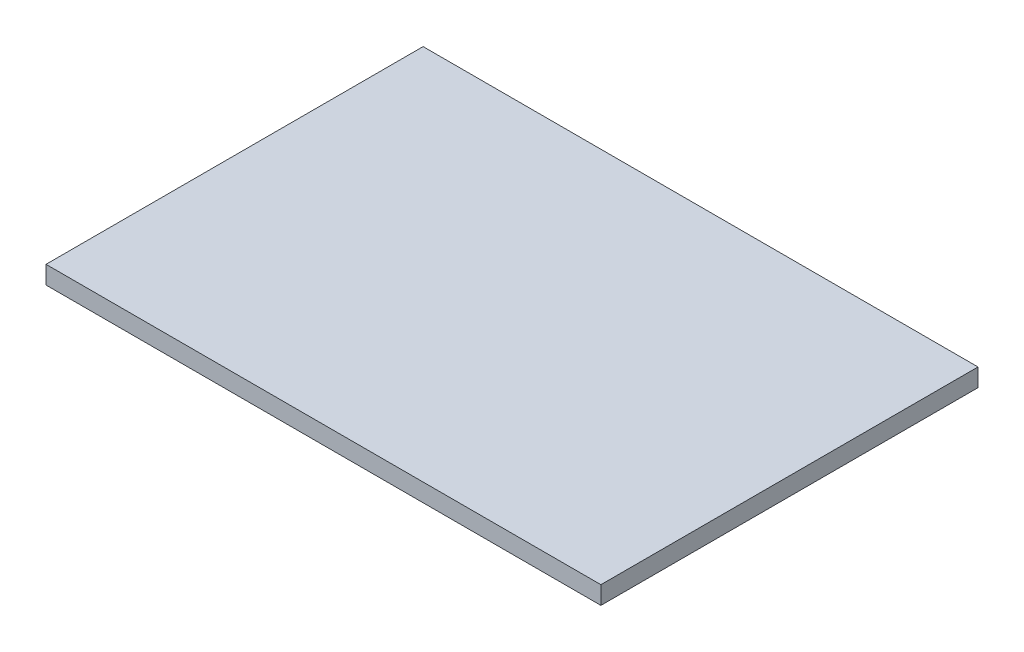
SolidWorks part; units mm, degrees
ref_plane "Front Plane" through (0, 0, 0) normal (0, 0, 1) x (1, 0, 0)
ref_plane "Top Plane" through (0, 0, 0) normal (0, 1, 0) x (1, 0, 0)
ref_plane "Right Plane" through (0, 0, 0) normal (1, 0, 0) x (0, 0, -1)
sketch "Sketch1" plane through (0, 0, 0) normal (0, 1, 0) x (1, 0, 0)
  line L1 (0, 0) -> (309, 0)
  line L2 (0, 0) -> (0, 210)
  line L3 (0, 210) -> (309, 210)
  line L4 (309, 0) -> (309, 210)
  dimension "D1" = 309
  dimension "D2" = 210
extrude "Boss-Extrude1" add sketch "Sketch1" along normal blind 10
